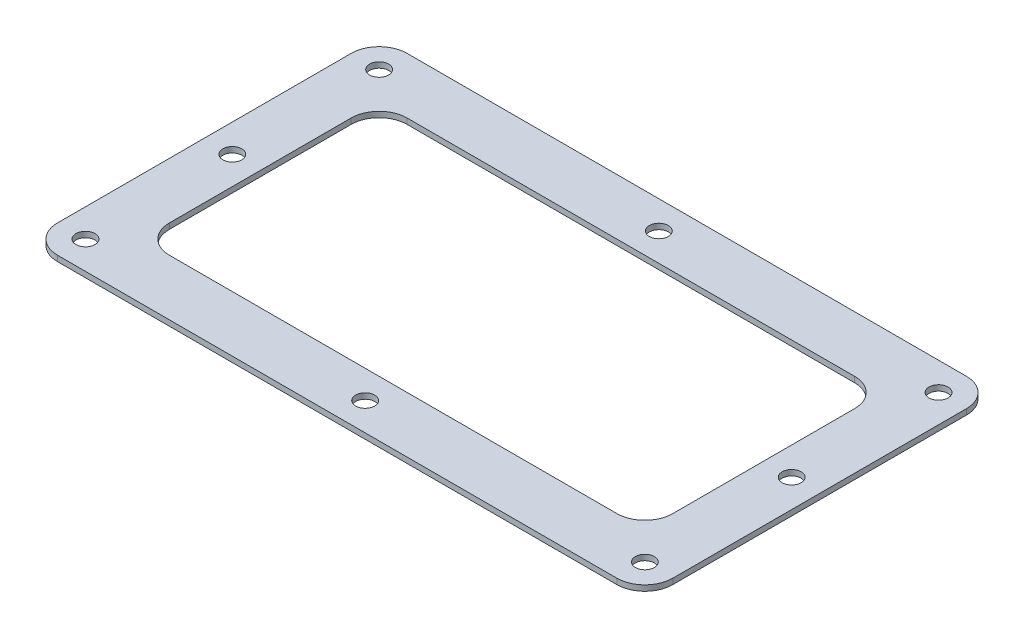
SolidWorks part; units mm, degrees
ref_plane "Front" through (0, 0, 0) normal (0, 0, 1) x (1, 0, 0)
ref_plane "Top" through (0, 0, 0) normal (0, 1, 0) x (1, 0, 0)
ref_plane "Right" through (0, 0, 0) normal (1, 0, 0) x (0, 0, -1)
sketch "Sketch1" plane through (0, 0, 0) normal (0, 1, 0) x (1, 0, 0)
  line L0 (-57.3253, 26.9036) -> (142.6747, 26.9036)
  line L1 (152.6747, 16.9036) -> (152.6747, -88.0964)
  line L2 (142.6747, -98.0964) -> (-57.3253, -98.0964)
  line L3 (-67.3253, -88.0964) -> (-67.3253, 16.9036)
  arc A0 (152.6747, -88.0964) -> (142.6747, -98.0964) centre (142.6747, -88.0964) cw
  arc A1 (142.6747, 26.9036) -> (152.6747, 16.9036) centre (142.6747, 16.9036) cw
  arc A2 (-57.3253, -98.0964) -> (-67.3253, -88.0964) centre (-57.3253, -88.0964) cw
  arc A3 (-57.3253, 26.9036) -> (-67.3253, 16.9036) centre (-57.3253, 16.9036) ccw
  point P8 (152.6747, 26.9036)
  point P11 (-67.3253, -98.0964)
  point P14 (-67.3253, 26.9036)
  dimension "D3" = 10
  dimension "D1" = 220
  dimension "D2" = 125
extrude "Boss-Extrude1" add sketch "Sketch1" along normal blind 2
hole_wizard "M8 Tapped Hole1" positions "Sketch2" profile "Sketch3" tap size "M8" standard "ISO" end condition through all
sketch "Sketch2" plane through (0, 2, 0) normal (0, 1, 0) x (1, 0, 0)
  point P0 (-57.3253, 16.9036)
  point P3 (142.6747, 16.9036)
  point P6 (-57.3253, -88.0964)
  point P9 (142.6747, -88.0964)
  point P12 (42.6747, -88.0964)
  point P14 (42.6747, 16.9036)
  point P16 (142.6747, -35.5964)
  point P18 (-57.3253, -35.5964)
sketch "Sketch3" plane through (-57.3253, 2, -16.9036) normal (1, 0, 0) x (0, 0, 1)
  line L0 (0, 0) -> (0, 2)
  line L1 (0, 2) -> (3.4, 2)
  line L2 (3.4, 2) -> (3.4, 0)
  line L5 (3.4, 0) -> (0, 0)
  line L11 (0, -6.35) -> (0, 107.95) construction
  dimension "Thru Tap Drill Dia." = 6.8
  dimension "Thru Tap Drill Depth" = 2
cosmetic thread "Hole Thread1" parameters "D2"=8
cosmetic thread "Hole Thread2" parameters "D2"=8
cosmetic thread "Hole Thread3" parameters "D2"=8
cosmetic thread "Hole Thread4" parameters "D2"=8
cosmetic thread "Hole Thread5" parameters "D2"=8
cosmetic thread "Hole Thread6" parameters "D2"=8
cosmetic thread "Hole Thread7" parameters "D2"=8
cosmetic thread "Hole Thread8" parameters "D2"=8
sketch "Sketch4" plane through (0, 2, 0) normal (0, 1, 0) x (1, 0, 0)
  line L0 (-57.3253, -35.5964) -> (-47.3253, -35.5964)
  line L1 (42.6747, -88.0964) -> (42.6747, -78.0964)
  line L2 (142.6747, -35.5964) -> (132.6747, -35.5964)
  line L3 (42.6747, 16.9036) -> (42.6747, 6.9036)
  line L4 (-47.3253, -35.5964) -> (-47.3253, -68.0964)
  line L5 (-37.3253, -78.0964) -> (122.6747, -78.0964)
  line L6 (132.6747, -68.0964) -> (132.6747, -3.0964)
  line L7 (122.6747, 6.9036) -> (-37.3253, 6.9036)
  line L8 (-47.3253, -3.0964) -> (-47.3253, -35.5964)
  arc A0 (122.6747, -78.0964) -> (132.6747, -68.0964) centre (122.6747, -68.0964) ccw
  arc A1 (132.6747, -3.0964) -> (122.6747, 6.9036) centre (122.6747, -3.0964) ccw
  arc A2 (-47.3253, -68.0964) -> (-37.3253, -78.0964) centre (-37.3253, -68.0964) ccw
  arc A3 (-37.3253, 6.9036) -> (-47.3253, -3.0964) centre (-37.3253, -3.0964) ccw
  dimension "D5" = 10
  dimension "D1" = 10
  dimension "D2" = 10
  dimension "D3" = 10
  dimension "D4" = 10
extrude "Cut-Extrude1" cut sketch "Sketch4" against normal blind 2 contours L7 A3 L8 L4 A2 L5 A0 L6 A1
